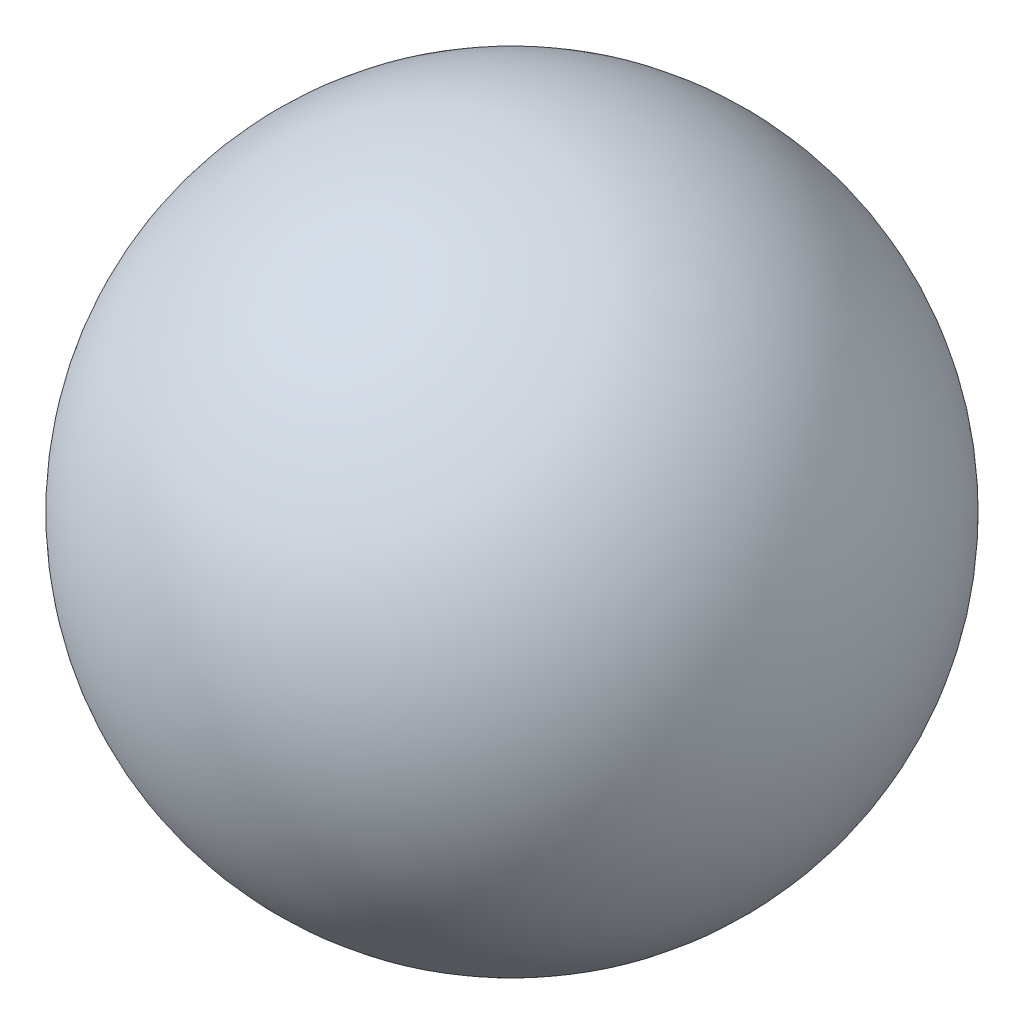
SolidWorks part; units mm, degrees
ref_plane "Front Plane" through (0, 0, 0) normal (0, 0, 1) x (1, 0, 0)
ref_plane "Top Plane" through (0, 0, 0) normal (0, 1, 0) x (1, 0, 0)
ref_plane "Right Plane" through (0, 0, 0) normal (1, 0, 0) x (0, 0, -1)
sketch "Sketch1" plane through (0, 0, 0) normal (1, 0, 0) x (0, 0, -1)
  line L0 (0, 6.35) -> (0, -6.35)
  arc A1 (0, -6.35) -> (0, 6.35) centre (0, 0) cw
  dimension "D1" = 6.35
revolve "Revolve1" add sketch "Sketch1" angle 360 about L0
